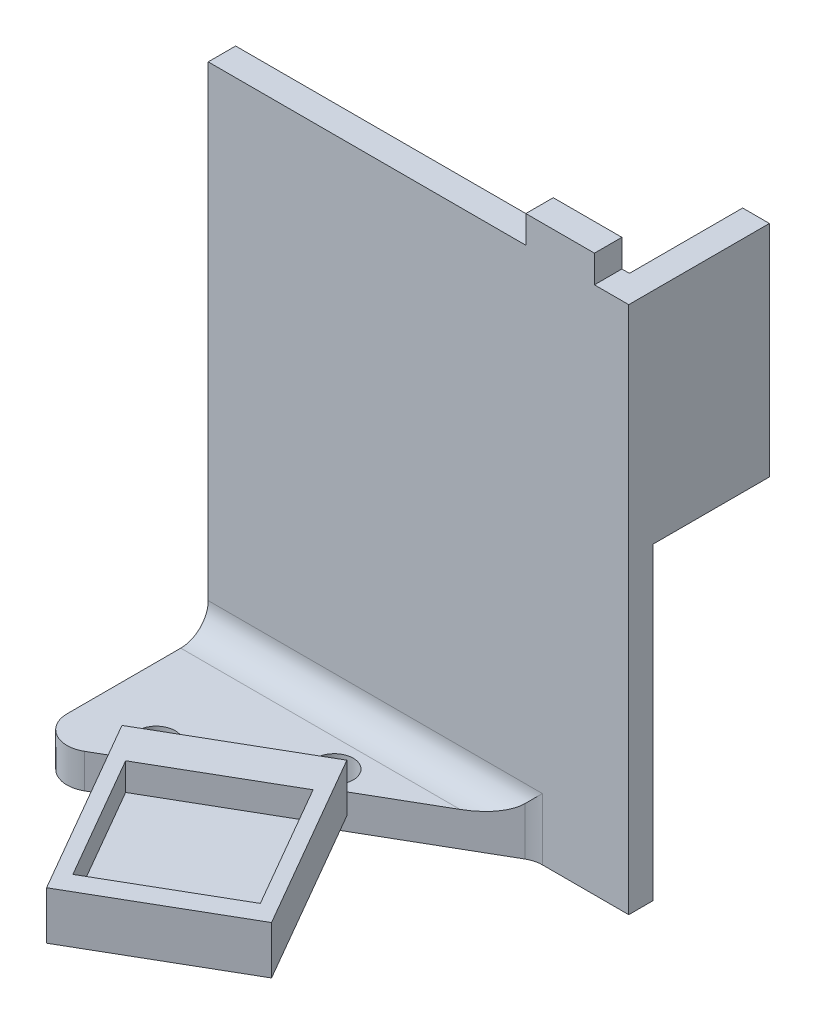
SolidWorks part; units mm, degrees
ref_plane "Front Plane" through (0, 0, 0) normal (0, 0, 1) x (1, 0, 0)
ref_plane "Top Plane" through (0, 0, 0) normal (0, 1, 0) x (1, 0, 0)
ref_plane "Right Plane" through (0, 0, 0) normal (1, 0, 0) x (0, 0, -1)
sketch "Sketch1" plane through (0, 0, 0) normal (0, 1, 0) x (1, 0, 0)
  line L0 (-48.3625, -26.4206) -> (-13.7215, -26.4206)
  line L2 (-0.7311, -29.9206) -> (-48.3625, -57.4206)
  line L3 (-48.3625, -57.4206) -> (-48.3625, -26.4206)
  line L4 (-0.7311, -29.9206) -> (12.9285, -29.9206)
  line L5 (12.9285, -29.9206) -> (12.9285, -26.4206)
  line L6 (12.9285, -26.4206) -> (-13.7215, -26.4206)
  circle A0 centre (-21.908, -37.9901) radius 2.75
  circle A1 centre (-38.3625, -47.4901) radius 2.75
  dimension "D5" = 26.65
  dimension "D3" = 5.5
  dimension "D6" = 5.5
  dimension "D1" = 30
  dimension "D2" = 10
  dimension "D4" = 31
  dimension "D8" = 19
extrude "Boss-Extrude1" add sketch "Sketch1" along normal blind 50
sketch "Sketch2" plane through (0, 50, 0) normal (0, 1, 0) x (1, 0, 0)
  line L0 (-48.3625, -26.4206) -> (12.9285, -26.4206)
  line L1 (12.9285, -26.4206) -> (12.9285, -4.4206)
  line L2 (12.9285, -4.4206) -> (1.6375, -4.4206)
  line L3 (1.6375, -4.4206) -> (1.6375, -11.9206)
  line L4 (1.6375, -11.9206) -> (-48.3625, -11.9206)
  line L5 (-48.3625, -11.9206) -> (-48.3625, -26.4206)
  line L6 (-37.4625, -15.6206) -> (-48.3625, -15.6206) construction
  line L7 (-37.4625, -15.6206) -> (-37.4625, -11.9206) construction
  circle A0 centre (-37.4625, -15.6206) radius 2.2
  dimension "D1" = 50
  dimension "D2" = 7.5
  dimension "D3" = 22
extrude "Boss-Extrude2" add sketch "Sketch2" against normal blind 5
sketch "Sketch3" plane through (0, 50, 0) normal (0, 1, 0) x (1, 0, 0)
  line L0 (-0.7311, -29.9206) -> (12.9285, -29.9206) construction
  line L1 (12.9285, -4.4206) -> (9.0285, -4.4206)
  line L2 (12.9285, -4.4206) -> (12.9285, -29.9206)
  line L3 (12.9285, -29.9206) -> (6.7785, -29.9206)
  line L4 (9.0285, -4.4206) -> (9.0285, -25.9206)
  line L5 (-48.3625, -11.9206) -> (-48.3625, -57.4206) construction
  line L6 (6.7785, -29.9206) -> (-48.3625, -29.9206)
  line L8 (9.0285, -25.9206) -> (-48.3625, -25.9206)
  line L9 (-48.3625, -29.9206) -> (-48.3625, -25.9206)
  dimension "D1" = 3.9
  dimension "D2" = 4
extrude "Boss-Extrude3" add sketch "Sketch3" along normal blind 32
sketch "Sketch4" plane through (0, 0, 4.4206) normal (0, 0, -1) x (-1, 0, 0)
  line L1 (4.3805, 10.5898) -> (-26.6267, 10.5898)
  line L2 (4.3805, 10.5898) -> (4.3805, 100.3777)
  line L3 (4.3805, 100.3777) -> (-26.6267, 100.3777)
  line L4 (-26.6267, 10.5898) -> (-26.6267, 100.3777)
extrude "Cut-Extrude1" cut sketch "Sketch4" against normal blind 5
fillet "Fillet2" radius 3 2 edges
sketch "Sketch6" plane through (0, 50, 0) normal (0, 1, 0) x (1, 0, 0)
  line L0 (-48.3625, -29.9206) -> (12.9285, -29.9206) construction
  line L1 (-56.2623, -29.9206) -> (20.5569, -29.9206)
  line L2 (-56.2623, -29.9206) -> (-56.2623, -66.6424)
  line L3 (-56.2623, -66.6424) -> (20.5569, -66.6424)
  line L4 (20.5569, -29.9206) -> (20.5569, -66.6424)
  dimension "D1" = 0
extrude "Cut-Extrude2" cut sketch "Sketch6" against normal blind 45
fillet "Fillet3" radius 4 3 edges at (-48.3625, 2.5, 57.4206) (-24.5468, 5, 29.9206)
sketch "Sketch7" plane through (12.7732, 0, 22.1239) normal (0.5, 0, 0.866) x (0.866, 0, -0.5)
  line L0 (-63.6653, 5) -> (-23.5935, 5) construction
  line L1 (-59.6653, 5) -> (-35.6653, 5)
  line L2 (-59.6653, 5) -> (-59.6653, 2)
  line L3 (-59.6653, 2) -> (-35.6653, 2)
  line L4 (-35.6653, 5) -> (-35.6653, 2)
  line L9 (-63.6653, 0) -> (-16.6653, 0) construction
  line L10 (-63.6653, 5) -> (-63.6653, 0) construction
  dimension "D1" = 24
  dimension "D2" = 2
  dimension "D3" = 4
extrude "Boss-Extrude4" add sketch "Sketch7" along normal blind 30
sketch "Sketch8" plane through (0, 5, 0) normal (0, 1, 0) x (1, 0, 0)
  line L0 (-23.6664, -74.3392) -> (-6.3459, -64.3392)
  line L1 (-6.3459, -64.3392) -> (-16.8459, -46.1527)
  line L2 (-16.8459, -46.1527) -> (-34.1664, -56.1527)
  line L3 (-34.1664, -56.1527) -> (-23.6664, -74.3392)
  line L4 (-3.1138, -65.9373) -> (-23.8984, -77.9373) construction
  line L5 (-3.1138, -65.9373) -> (-18.1138, -39.9565) construction
  line L6 (-23.8984, -77.9373) -> (-38.8984, -51.9565) construction
  line L7 (-18.1138, -39.9565) -> (-38.8984, -51.9565)
  line L8 (-38.8984, -51.9565) -> (-23.8984, -77.9373)
  line L9 (-23.8984, -77.9373) -> (-3.1138, -65.9373)
  line L10 (-3.1138, -65.9373) -> (-18.1138, -39.9565)
  dimension "D1" = 3
  dimension "D2" = 2
  dimension "D3" = 2
  dimension "D4" = 21
extrude "Boss-Extrude5" add sketch "Sketch8" along normal blind 4
sketch "Sketch9" plane through (0, 0, 29.9206) normal (0, 0, 1) x (1, 0, 0)
  line L1 (-48.3625, 82) -> (21.6375, 82)
  line L2 (-48.3625, 82) -> (-48.3625, 77)
  line L3 (-48.3625, 77) -> (21.6375, 77)
  line L4 (21.6375, 82) -> (21.6375, 77)
  dimension "D1" = 70
  dimension "D2" = 5
extrude "Cut-Extrude3" cut sketch "Sketch9" against normal blind 30
ref_plane "Plane1" through (0, 45, 0) normal (0, 1, 0) x (1, 0, 0)
sketch "Sketch11" plane through (0, 45, 0) normal (0, 1, 0) x (1, 0, 0)
  line L0 (12.9285, -29.9206) -> (12.9285, -27.9206) construction
  line L1 (12.9285, -9.4206) -> (12.9285, -29.9206) construction
  line L2 (12.9285, -27.9206) -> (7.9285, -27.9206) construction
  line L4 (7.9285, -29.9206) -> (-2.0715, -29.9206)
  line L5 (-2.0715, -29.9206) -> (-2.0715, -27.9206)
  line L8 (7.9285, -27.9206) -> (7.9285, -25.9206) construction
  line L9 (-48.3625, -25.9206) -> (9.0285, -25.9206) construction
  line L11 (-2.0715, -27.9206) -> (-2.0715, -25.9206)
  line L12 (9.0285, -25.9206) -> (-48.3625, -25.9206) construction
  line L13 (-2.0715, -25.9206) -> (7.9285, -25.9206)
  line L15 (7.9285, -25.9206) -> (7.9285, -29.9206)
extrude "Boss-Extrude6" add sketch "Sketch11" along normal blind 36
